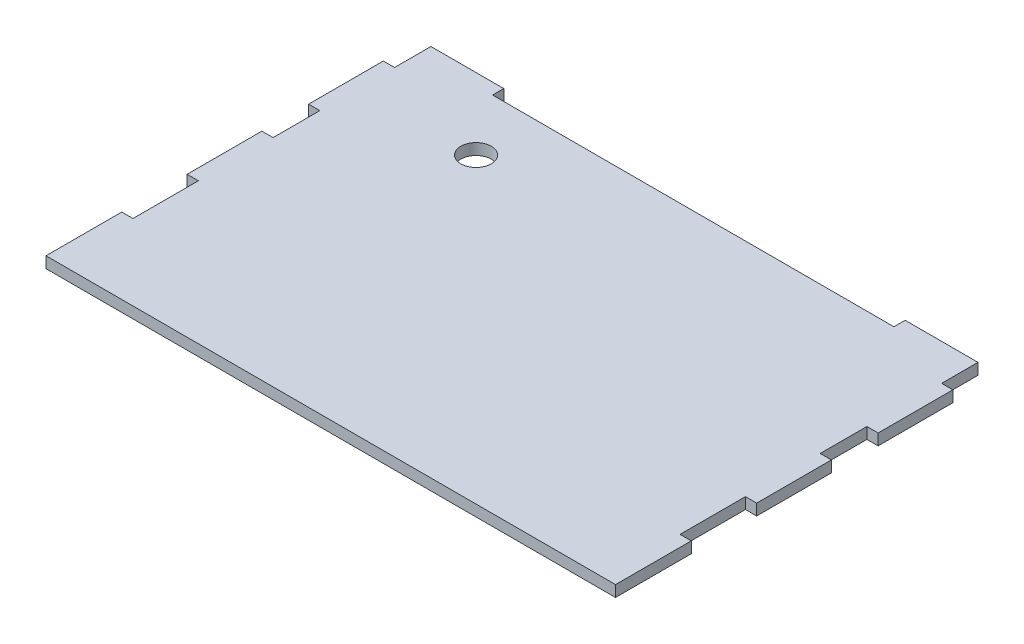
SolidWorks part; units mm, degrees
ref_plane "Front Plane" through (0, 0, 0) normal (1, 0, 0) x (0, 1, 0)
ref_plane "Top Plane" through (0, 0, 0) normal (0, 0, 1) x (0, 1, 0)
ref_plane "Right Plane" through (0, 0, 0) normal (0, 1, 0) x (-1, 0, 0)
sketch "Sketch1" plane through (0, 0, 0) normal (0, 1, 0) x (-1, 0, 0)
  line L0 (-79.8276, -104.4828) -> (-79.8276, -98.4828)
  line L1 (-124.8276, 95.5172) -> (179.9724, 95.5172)
  line L2 (-124.8276, 95.5172) -> (-124.8276, 54.9772)
  line L3 (-118.8276, -104.4828) -> (-79.8276, -104.4828)
  line L4 (179.9724, 95.5172) -> (179.9724, 54.9772)
  line L5 (-79.8276, -98.4828) -> (134.9724, -98.4828)
  line L6 (134.9724, -98.4828) -> (134.9724, -104.4828)
  line L7 (134.9724, -104.4828) -> (173.9724, -104.4828)
  line L8 (-208.0753, -85.0228) -> (281.8886, -85.0228) construction
  line L9 (-233.4089, -45.0228) -> (226.3701, -45.0228) construction
  line L10 (-219.3946, -20.0228) -> (278.6545, -20.0228) construction
  line L11 (-219.3946, 19.9772) -> (266.8658, 19.9772) construction
  line L12 (173.9724, -104.4828) -> (173.9724, -85.0228)
  line L13 (173.9724, -85.0228) -> (179.9724, -85.0228)
  line L14 (179.9724, -45.0228) -> (173.9724, -45.0228)
  line L15 (173.9724, -45.0228) -> (173.9724, -20.0228)
  line L16 (173.9724, -20.0228) -> (179.9724, -20.0228)
  line L17 (-201.5784, 54.9772) -> (242.2612, 54.9772) construction
  line L18 (179.9724, 54.9772) -> (173.9724, 54.9772)
  line L19 (173.9724, 54.9772) -> (173.9724, 19.9772)
  line L20 (173.9724, 19.9772) -> (179.9724, 19.9772)
  line L21 (27.5724, -98.4828) -> (27.5724, 134.7945) construction
  line L22 (179.9724, 19.9772) -> (179.9724, -20.0228)
  line L23 (179.9724, -45.0228) -> (179.9724, -85.0228)
  line L24 (-118.8276, 54.9772) -> (-118.8276, 19.9772)
  line L25 (-118.8276, -104.4828) -> (-118.8276, -85.0228)
  line L26 (-118.8276, -85.0228) -> (-124.8276, -85.0228)
  line L27 (-124.8276, -45.0228) -> (-118.8276, -45.0228)
  line L28 (-118.8276, -45.0228) -> (-118.8276, -20.0228)
  line L29 (-118.8276, -20.0228) -> (-124.8276, -20.0228)
  line L30 (-118.8276, 19.9772) -> (-124.8276, 19.9772)
  line L31 (-124.8276, 54.9772) -> (-118.8276, 54.9772)
  line L32 (-124.8276, 19.9772) -> (-124.8276, -20.0228)
  line L33 (-124.8276, -45.0228) -> (-124.8276, -85.0228)
  dimension "D2" = 6
  dimension "D3" = 6
  dimension "D4" = 45
  dimension "D5" = 6
  dimension "D6" = 19.46
  dimension "D7" = 40
  dimension "D8" = 25
  dimension "D9" = 40
  dimension "D10" = 35
  dimension "D11" = 6
extrude "Boss-Extrude1" add sketch "Sketch1" along normal blind 6
sketch "Sketch2" plane through (0, 0, 0) normal (0, -1, 0) x (1, 0, 0)
  circle A0 centre (-111.5855, -66.2571) radius 8.1571
extrude "Cut-Extrude1" cut sketch "Sketch2" against normal blind 10
